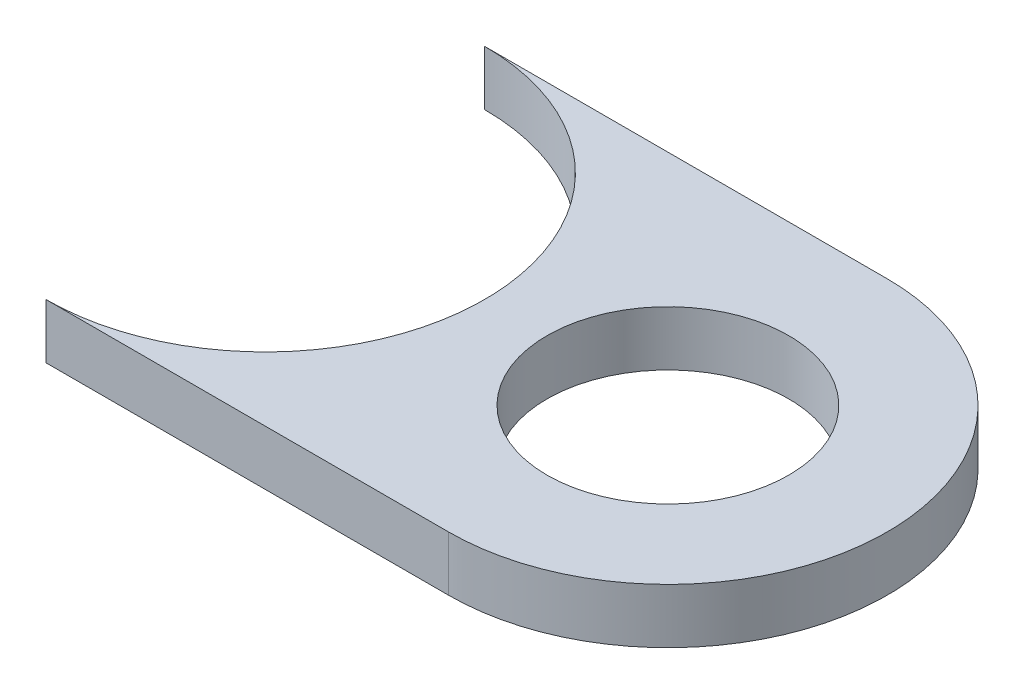
SolidWorks part; units mm, degrees
ref_plane "Front Plane" through (0, 0, 0) normal (0, 0, 1) x (1, 0, 0)
ref_plane "Top Plane" through (0, 0, 0) normal (0, 1, 0) x (1, 0, 0)
ref_plane "Right Plane" through (0, 0, 0) normal (1, 0, 0) x (0, 0, -1)
sketch "Sketch1" plane through (0, 0, 0) normal (0, 1, 0) x (1, 0, 0)
  line L0 (0, 0) -> (-23.3172, 0) construction
  line L1 (-23.3172, 12.7) -> (0, 12.7)
  line L2 (-23.3172, -12.7) -> (0, -12.7)
  circle A0 centre (0, 0) radius 7.0002
  arc A1 (-23.3172, -12.7) -> (-23.3172, 12.7) centre (-23.3172, 0) ccw
  arc A2 (0, -12.7) -> (0, 12.7) centre (0, 0) ccw
extrude "Boss-Extrude1" add sketch "Sketch1" along normal blind 3.175
sketch "Sketch2" plane through (0, 3.175, 0) normal (0, 1, 0) x (1, 0, 0)
  line L0 (0, 12.7) -> (0, 9.525)
  line L1 (0, 9.525) -> (-14.9169, 9.525)
  arc A0 (-23.3172, -12.7) -> (-23.3172, 12.7) centre (-23.3172, 0) ccw construction
  dimension "D1" = 14.9169
